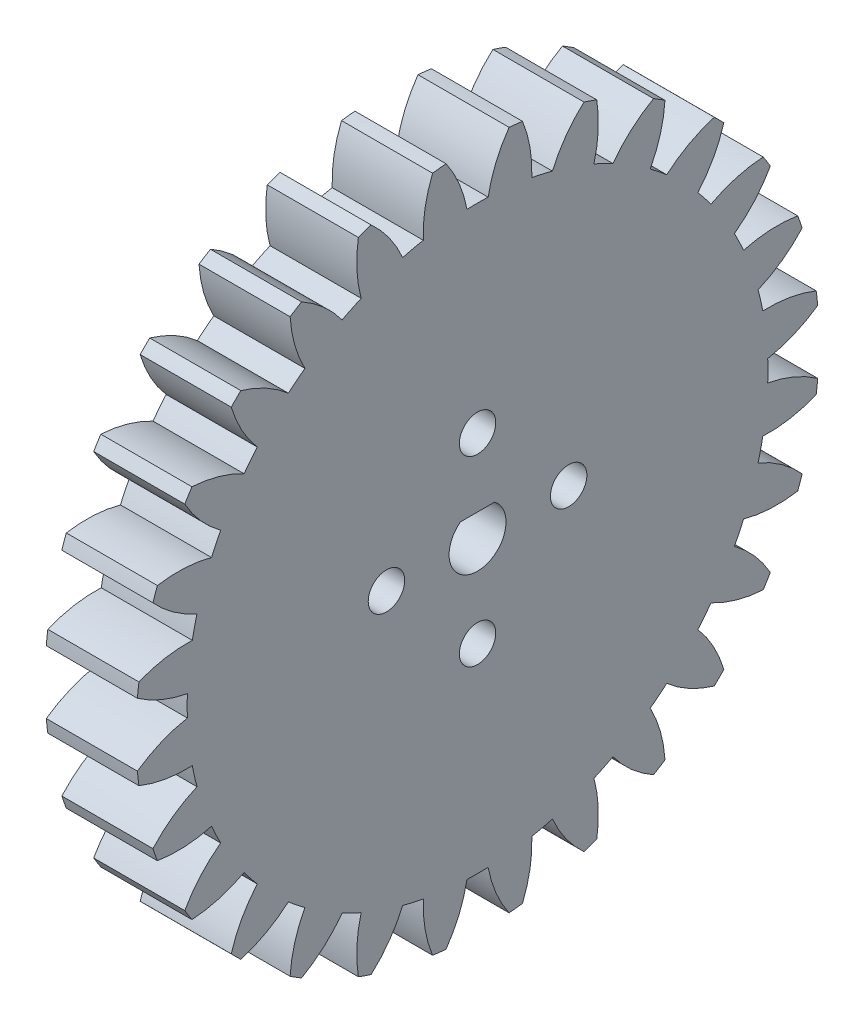
SolidWorks part; units mm, degrees
material "ABS generico"
ref_plane "Plane1" through (0, 0, 0) normal (0, 0, 1) x (1, 0, 0)
ref_plane "Plane2" through (0, 0, 0) normal (0, 1, 0) x (1, 0, 0)
ref_plane "Plane3" through (0, 0, 0) normal (1, 0, 0) x (0, 0, -1)
sketch "HoldingSke" plane through (0, 0, 0) normal (0, 1, 0) x (1, 0, 0)
  line L0 (0, 0) -> (0.4415, -0.2347)
  line L1 (-15, 0) -> (100, 0) construction
  line L2 (0, 0) -> (-2.1039, 2.3779)
  line L3 (0, 0) -> (-11.863, 4.5341)
  line L4 (0, 0) -> (7.6251, 4.0544)
  line L5 (0, 0) -> (-46.8476, -17.4728)
  line L6 (0, 0) -> (-9.9476, -6.7116)
  line L7 (-2.1039, 2.3779) -> (8.6586, 51.2059)
  line L8 (-76.2, 54.61) -> (-76.1, 54.61)
  line L9 (-71.009, 38.7566) -> (-53.1078, 45.2721)
  line L10 (-76.2, 71.12) -> (104.1128, 71.12)
  line L11 (0, 0) -> (-12, 0)
  line L12 (-76.2, 101.6) -> (-76.133, 101.6)
  line L13 (24.9733, 27.94) -> (52.9518, 28.4284)
  line L14 (24.9733, 27.94) -> (24.9743, 27.94)
  line L15 (24.9733, 27.94) -> (100.4006, 29.5858)
  line L16 (-63.627, -2) -> (-12.827, -2)
  circle A0 centre (0, 0) radius 0.1
  circle A1 centre (0, 0) radius 25.499
  circle A2 centre (0, 0) radius 37.5
  circle A3 centre (0, 0) radius 0.1
  dimension "MHD" = 50.998
  dimension "Hub_dia" = 75
  dimension "Bore" = 0.2
  dimension "MBD" = 0.2
  dimension "Num_teeth" = 28
  dimension "Pitch" = 0.5
  dimension "Overall_len" = 50
  dimension "Show_teeth" = 28
  dimension "Thickness" = 12
  dimension "OAL" = 50.0001
  dimension "T_dim" = 0.1
  dimension "Ap" = 20
  dimension "H" = 19.05
  dimension "Pitch_radius" = 180.3128
  dimension "Width" = 12
  dimension "Backlash" = 0.067
  dimension "Addendum_fac" = 1
  dimension "Dedendum_fac" = 1.25
  dimension "Clearance_fac" = 0.25
  dimension "Dedendum_add" = 0.001
  dimension "Module" = 2
sketch "BasProSke" plane through (0, 0, 0) normal (0, 1, 0) x (1, 0, 0)
  line L0 (-10, 0) -> (60, 0) construction
  line L1 (0, 0) -> (0, 30)
  line L2 (0, 0) -> (8, 0)
  line L3 (8, 0) -> (8, 30)
  line L4 (8, 30) -> (0, 30)
  dimension "Thickness" = 8
  dimension "Diameter" = 60
revolve "Base-Revolve" add sketch "BasProSke" angle 360 about L0
sketch "TooCutSke" plane through (0, 0, 0) normal (1, 0, 0) x (0, 0, -1)
  line L1 (0, 0) -> (0, 107) construction
  line L2 (0, 0) -> (-1.6872, 27.9491) construction
  line L3 (0, 0) -> (-6.2616, 55.5729) construction
  line L4 (-1.6872, 27.9491) -> (-3.1308, 27.7865) construction
  arc A0 (0.9285, 25.4821) -> (-0.9285, 25.4821) centre (0, 0) ccw
  arc A1 (2.7859, 29.8959) -> (-2.7859, 29.8959) centre (0, 0) ccw
  circle A2 centre (0, 0) radius 28 construction
  circle A3 centre (0, 0) radius 26.3114 construction
  arc A4 (-0.9285, 25.4821) -> (-2.7859, 29.8959) centre (-11.9418, 23.4453) ccw
  arc A5 (2.7859, 29.8959) -> (0.9285, 25.4821) centre (11.9418, 23.4453) ccw
  dimension "Root_dia" = 50.998
  dimension "Overcut_dia" = 60.0508
  dimension "Pitch_dia" = 56
  dimension "Base_dia" = 52.6228
  dimension "Flank_rad" = 11.2
  dimension "Half_ang" = 6.429
  dimension "Half_CT" = 1.4527
extrude "ToothCut" cut sketch "TooCutSke" along normal through all
fillet "Breaks" [suppressed] radius 0.04
fillet "RootFillets" [suppressed] radius 0.501
pattern_circular "TeethCuts" count 28 every 12.857 about axis through (-10, 0, 0) along (1, 0, 0) of "ToothCut", "RootFillets", "Breaks"
sketch "HubNeaOneSke" plane through (0, 0, 0) normal (-1, 0, 0) x (0, 0, 1)
  circle A0 centre (0, 0) radius 25.499
  dimension "Diameter" = 50.998
extrude "HubNearOne" [suppressed] add sketch "HubNeaOneSke" along normal blind 42.0001
sketch "HubNeaBotSke" plane through (0, 0, 0) normal (-1, 0, 0) x (0, 0, 1)
  circle A0 centre (0, 0) radius 25.499
  dimension "Diameter" = 50.998
extrude "HubNearBoth" [suppressed] add sketch "HubNeaBotSke" along normal blind 21
ref_plane "FarPln" through (8, 0, 0) normal (1, 0, 0) x (0, 0, -1)
sketch "HubFarSke" plane through (8, 0, 0) normal (1, 0, 0) x (0, 0, -1)
  circle A0 centre (0, 0) radius 25.499
  dimension "Diameter" = 50.998
extrude "HubFar" [suppressed] add sketch "HubFarSke" along normal blind 21
sketch "BorSke" plane through (0, 0, 0) normal (1, 0, 0) x (0, 0, -1)
  circle A0 centre (0, 0) radius 0.1
  dimension "Diameter" = 0.2
extrude "Bore" cut sketch "BorSke" along normal mid plane 100.0001
sketch "KeySke" plane through (0, 0, 0) normal (1, 0, 0) x (0, 0, -1)
  line L0 (-0.05, 0) -> (-0.05, 0.2)
  line L1 (-0.05, 0.2) -> (0.05, 0.2)
  line L2 (0.05, 0.2) -> (0.05, 0)
  line L3 (0, 0) -> (0, 34) construction
  line L4 (-0.05, 0) -> (0.05, 0)
  dimension "Offset" = 0.2
  dimension "Width" = 0.1
extrude "Keyway" [suppressed] cut sketch "KeySke" along normal mid plane 100.0001
pattern_circular "Keyway2" [suppressed] count 2 every 90 about axis through (-10, 0, 0) along (1, 0, 0)
sketch "Schizzo1" plane through (8, 0, 0) normal (1, 0, 0) x (0, 0, -1)
  line L0 (-1.5, 2) -> (1.5, 2)
  arc A0 (-1.5, 2) -> (1.5, 2) centre (0, 0) ccw
  dimension "D1" = 5
  dimension "D2" = 2
extrude "Taglio-Estrusione1" cut sketch "Schizzo1" against normal blind 30
sketch "Schizzo2" plane through (0, 0, 0) normal (-1, 0, 0) x (0, 0, 1)
  circle A0 centre (0, 0) radius 8 construction
  circle A1 centre (0, 8) radius 1.6
  circle A2 centre (8, 0) radius 1.6
  circle A3 centre (0, -8) radius 1.6
  circle A4 centre (-8, 0) radius 1.6
  dimension "D1" = 16
  dimension "D2" = 3.2
extrude "Taglio-Estrusione2" cut sketch "Schizzo2" against normal blind 10
equation "' \"Module@HoldingSke\" = 6.35"
equation "' \"Num_teeth@HoldingSke\" = 12"
equation "' \"Ap@HoldingSke\" =  20"
equation "' \"Ap@HoldingSke\" = 20"
equation "' \"Width@HoldingSke\" = 0.5 * 25.4"
equation "' \"Hub_dia@HoldingSke\"= 1 * 25.4"
equation "' \"Hub_dia@HoldingSke\" = 1 * 25.4"
equation "' \"Overall_len@HoldingSke\" = 1.0 * 25.4"
equation "' \"Bore@HoldingSke\" = 0.75 * 25.4"
equation "' \"T_dim@HoldingSke\" = 0.1 * 25.4"
equation "' \"Width@KeySke\" = 0.25 * 25.4"
equation "' \"Show_teeth@HoldingSke\" = 13"
equation "' \"Backlash@HoldingSke\" = 0.009 * 25.4"
equation "' \"Addendum_fac@HoldingSke\" = 1.0"
equation "' \"Dedendum_fac@HoldingSke\" = 1.25"
equation "' \"Dedendum_add@HoldingSke\" = 0.00005 * 25.4"
equation "' \"Clearance_fac@HoldingSke\" = 0.25"
equation "\"Pitch@HoldingSke\" = 1 / \"Module@HoldingSke\""
equation "\"Overcut_dia@TooCutSke\" = (\"Num_teeth@HoldingSke\" + 2 * \"Addendum_fac@HoldingSke\") / \"Pitch@HoldingSke\" + 0.002 * 25.4"
equation "\"Pitch_dia@TooCutSke\" = \"Num_teeth@HoldingSke\" / \"Pitch@HoldingSke\""
equation "\"Base_dia@TooCutSke\" = \"Num_teeth@HoldingSke\" / \"Pitch@HoldingSke\" * cos((\"Ap@HoldingSke\"  * 3.14159265 / 180))"
equation "\"Root_dia@TooCutSke\" = (\"Num_teeth@HoldingSke\" + 2) / \"Pitch@HoldingSke\" - 2 * (\"Addendum_fac@HoldingSke\" + \"Dedendum_fac@HoldingSke\") / \"Pitch@HoldingSke\" - \"Dedendum_add@HoldingSke\" * 2"
equation "\"Half_ang@TooCutSke\" = 180 / \"Num_teeth@HoldingSke\""
equation "\"Half_CT@TooCutSke\" = \"Num_teeth@HoldingSke\" / \"Pitch@HoldingSke\" * sin((3.14159265 / 2 / \"Num_teeth@HoldingSke\")) / 2 - 7 * \"Backlash@HoldingSke\" / 4"
equation "\"Flank_rad@TooCutSke\" = \"Num_teeth@HoldingSke\" / \"Pitch@HoldingSke\" / 5"
equation "\"Radius@RootFillets\" = \"Clearance_fac@HoldingSke\" / \"Pitch@HoldingSke\" + \"Dedendum_add@HoldingSke\""
equation "\"Break_rad@Breaks\" = 0.02 / \"Pitch@HoldingSke\""
equation "\"Thickness@HoldingSke\" = \"Width@HoldingSke\""
equation "\"OAL@HoldingSke\" = \"Thickness@HoldingSke\""
equation "\"MHD@HoldingSke\" = (\"Num_teeth@HoldingSke\" + 2) / \"Pitch@HoldingSke\" - 2 * (\"Addendum_fac@HoldingSke\" + \"Dedendum_fac@HoldingSke\")  / \"Pitch@HoldingSke\" - \"Dedendum_add@HoldingSke\" * 2"
equation "\"MBD@HoldingSke\" = (\"Num_teeth@HoldingSke\" + 2) / \"Pitch@HoldingSke\" - 2 * (\"Addendum_fac@HoldingSke\" + \"Dedendum_fac@HoldingSke\")  / \"Pitch@HoldingSke\" - \"Dedendum_add@HoldingSke\" * 2 - 0.002 * 25.4"
equation "\"MHD@HoldingSke\" = ((sgn( \"MHD@HoldingSke\" - \"Hub_dia@HoldingSke\" )-1)*( \"MHD@HoldingSke\" - \"Hub_dia@HoldingSke\" ))/-2+ \"Hub_dia@HoldingSke\""
equation "\"MBD@HoldingSke\" = ((sgn( \"MBD@HoldingSke\" - \"Bore@HoldingSke\" )-1)*( \"MBD@HoldingSke\" - \"Bore@HoldingSke\" ))/-2+ \"Bore@HoldingSke\""
equation "\"OAL@HoldingSke\" = ((sgn( \"OAL@HoldingSke\" - \"Overall_len@HoldingSke\" )+1)*( \"OAL@HoldingSke\" - \"Overall_len@HoldingSke\" ))/2 + \"Overall_len@HoldingSke\" + 0.000002 * 25.4"
equation "\"Num_teeth@TeethCuts\" = int( \"Show_teeth@HoldingSke\" ) + 1"
equation "\"Num_teeth@TeethCuts\" = ((sgn( \"Num_teeth@TeethCuts\" - \"Num_teeth@HoldingSke\" )-1)*( \"Num_teeth@TeethCuts\" - \"Num_teeth@HoldingSke\" ))/-2+ \"Num_teeth@HoldingSke\""
equation "\"Num_teeth@TeethCuts\" = ((sgn( \"Num_teeth@TeethCuts\" - 2.0)+1)*( \"Num_teeth@TeethCuts\" - 2.0))/2 +2.0"
equation "\"Angle@TeethCuts\" = 360.0 / \"Num_teeth@HoldingSke\""
equation "\"Diameter@BasProSke\" = (\"Num_teeth@HoldingSke\" + 2 * \"Addendum_fac@HoldingSke\") / \"Pitch@HoldingSke\""
equation "' \"Fillet_rad@BasProSke\" =  \"Thickness@HoldingSke\" * 0.05"
equation "' \"Fillet_rad@BasProSke\" = \"Thickness@HoldingSke\" * 0.05"
equation "\"MHD@HoldingSke\" = ((sgn( \"MHD@HoldingSke\" - \"Root_dia@TooCutSke\" )-1)*( \"MHD@HoldingSke\" - \"Root_dia@TooCutSke\" ))/-2+ \"Root_dia@TooCutSke\""
equation "\"Diameter@HubNeaOneSke\" = \"MHD@HoldingSke\""
equation "\"Length@HubNearOne\" = \"OAL@HoldingSke\" - \"Thickness@BasProSke\""
equation "\"Diameter@HubNeaBotSke\" = \"MHD@HoldingSke\""
equation "\"Length@HubNearBoth\" = ( \"OAL@HoldingSke\" - \"Thickness@BasProSke\" ) / 2.0"
equation "\"Thickness@FarPln\" = \"Thickness@BasProSke\""
equation "\"Diameter@HubFarSke\" = \"MHD@HoldingSke\""
equation "\"Length@HubFar\" = ( \"OAL@HoldingSke\" - \"Thickness@BasProSke\" ) / 2.0"
equation "\"Diameter@BorSke\" = \"MBD@HoldingSke\""
equation "\"D1@Bore\" = \"OAL@HoldingSke\" * 2.0"
equation "\"D1@Keyway\" = \"OAL@HoldingSke\" * 2.0"
equation "\"Offset@KeySke\" = \"T_dim@HoldingSke\" + \"MBD@HoldingSke\" / 2.0"
